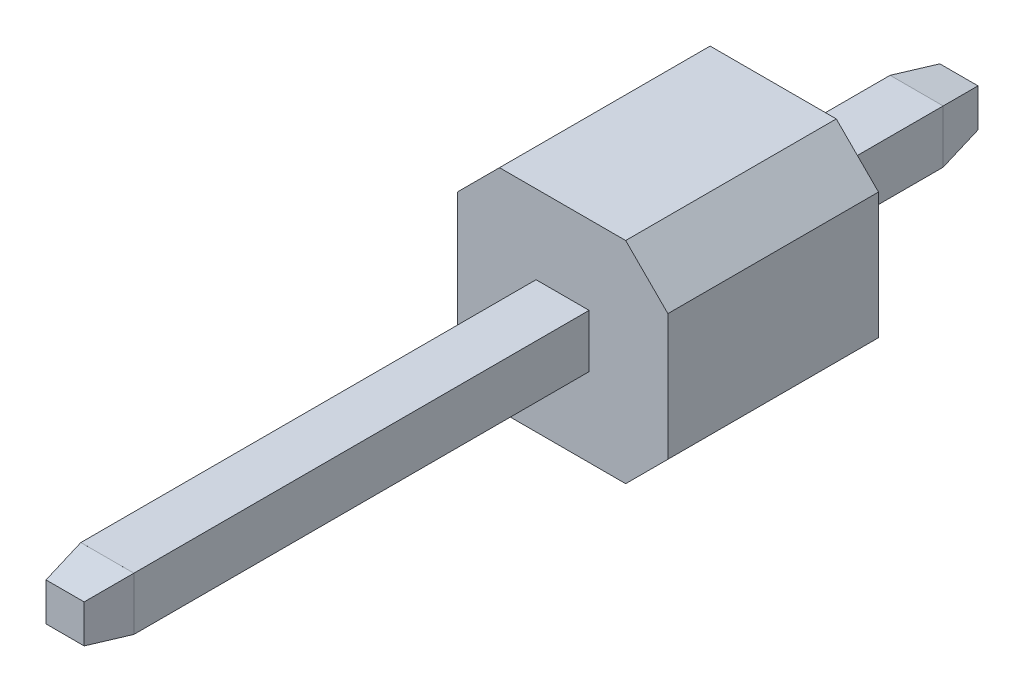
SolidWorks part; units mm, degrees
ref_plane "正面" through (0, 0, 0) normal (0, 0, 1) x (1, 0, 0)
ref_plane "平面" through (0, 0, 0) normal (0, 1, 0) x (1, 0, 0)
ref_plane "右側面" through (0, 0, 0) normal (1, 0, 0) x (0, 0, -1)
sketch "ｽｹｯﾁ1" plane through (0, 0, 0) normal (0, 0, 1) x (1, 0, 0)
  line L1 (-1.27, 1.27) -> (1.27, 1.27)
  line L2 (-1.27, 1.27) -> (-1.27, -1.27)
  line L3 (-1.27, -1.27) -> (1.27, -1.27)
  line L4 (1.27, 1.27) -> (1.27, -1.27)
  line L5 (-1.27, 1.27) -> (1.27, -1.27) construction
  line L6 (-1.27, -1.27) -> (1.27, 1.27) construction
  point P0 (0, 0)
  dimension "D1" = 2.54
extrude "ﾎﾞｽ - 押し出し1" add sketch "ｽｹｯﾁ1" along normal blind 2.54
sketch "ｽｹｯﾁ2" plane through (0, 0, 0) normal (0, 0, 1) x (1, 0, 0)
  line L1 (-0.32, 0.32) -> (0.32, 0.32)
  line L2 (-0.32, 0.32) -> (-0.32, -0.32)
  line L3 (-0.32, -0.32) -> (0.32, -0.32)
  line L4 (0.32, 0.32) -> (0.32, -0.32)
  line L5 (-0.32, 0.32) -> (0.32, -0.32) construction
  line L6 (-0.32, -0.32) -> (0.32, 0.32) construction
  point P0 (0, 0)
  dimension "D1" = 0.64
extrude "ﾎﾞｽ - 押し出し2" add sketch "ｽｹｯﾁ2" along normal blind 8.03 and the other way blind 1.73
sketch "ｽｹｯﾁ3" plane through (0, 0, -1.73) normal (0, 0, -1) x (-1, 0, 0)
  line L1 (0.23, 0.23) -> (-0.23, 0.23)
  line L2 (0.23, 0.23) -> (0.23, -0.23)
  line L3 (0.23, -0.23) -> (-0.23, -0.23)
  line L4 (-0.23, 0.23) -> (-0.23, -0.23)
  point P6 (0, -0.23)
  point P8 (-0.23, 0)
  dimension "D1" = 0.46
extrude "ﾎﾞｽ - 押し出し3" add sketch "ｽｹｯﾁ3" along normal blind 0.51
sketch "ｽｹｯﾁ4" plane through (0, 0, 8.03) normal (0, 0, 1) x (1, 0, 0)
  line L1 (0.23, 0.23) -> (-0.23, 0.23)
  line L2 (0.23, 0.23) -> (0.23, -0.23)
  line L3 (0.23, -0.23) -> (-0.23, -0.23)
  line L4 (-0.23, 0.23) -> (-0.23, -0.23)
  point P6 (0, -0.23)
  point P8 (-0.23, 0)
  dimension "D1" = 0.46
extrude "ﾎﾞｽ - 押し出し4" add sketch "ｽｹｯﾁ4" along normal blind 0.51
draft "抜き勾配2" type of draft neutral plane draft angle 10 faces to draft 4 face at (0, -0.23, 8.285) face at (-0.23, 0, 8.285) face at (0, 0.23, 8.285) face at (0.23, 0, 8.285) neutral plane through (0, 0, 8.54) neutral plane normal (0, 0, 1) parameters "D1"=10
draft "抜き勾配3" type of draft neutral plane draft angle 10 faces to draft 4 face at (-0.23, 0, -1.985) face at (0, -0.23, -1.985) face at (0.23, 0, -1.985) face at (0, 0.23, -1.985) neutral plane through (0, 0, -2.24) neutral plane normal (0, 0, -1) parameters "D1"=10
chamfer "面取り1" distance 0.5091 4 edges at (-1.27, -1.27, 1.27) (-1.27, 1.27, 1.27) (1.27, 1.27, 1.27) (1.27, -1.27, 1.27)
